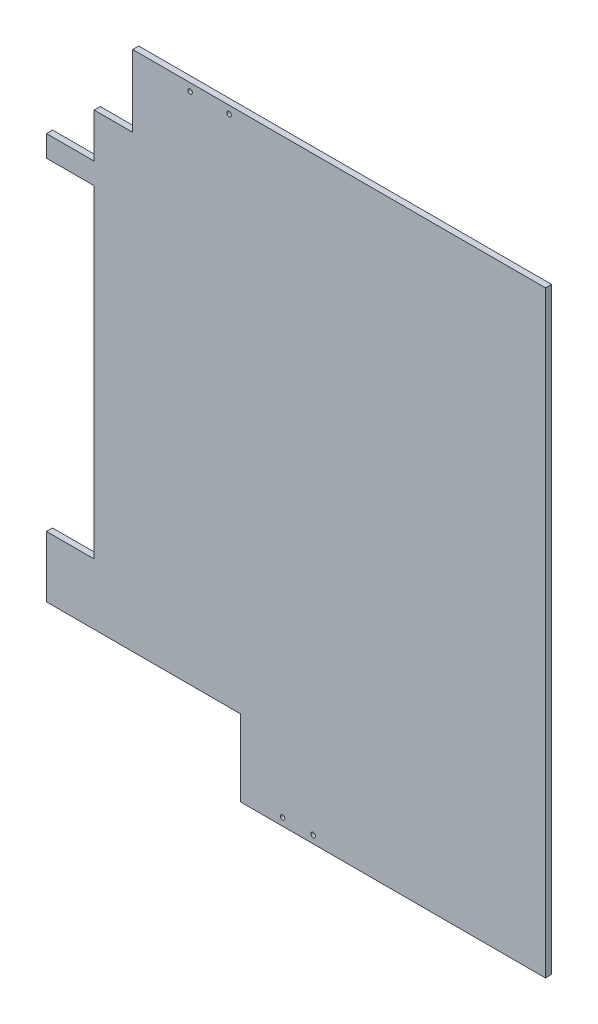
SolidWorks part; units mm, degrees
material "Balsa"
ref_plane "Front Plane" through (0, 0, 0) normal (0, 0, 1) x (1, 0, 0)
ref_plane "Top Plane" through (0, 0, 0) normal (0, 1, 0) x (1, 0, 0)
ref_plane "Right Plane" through (0, 0, 0) normal (1, 0, 0) x (0, 0, -1)
sketch "Sketch1" plane through (0, 0, 0) normal (0, 0, 1) x (1, 0, 0)
  line L0 (-5.7823, -13) -> (25.5, -13)
  line L2 (-5.7823, 1) -> (-5.7823, -13)
  line L5 (24.5, -14) -> (-24.5, -14) construction
  line L6 (321.5, -265) -> (321.5, 30)
  line L7 (-5.8246, -265) -> (65.6329, -265)
  line L8 (-5.8246, -265) -> (-5.8246, -225)
  line L11 (-5.8246, -265) -> (65.6329, -225) construction
  line L12 (-5.8246, -225) -> (65.6329, -265) construction
  line L15 (321.5, -265) -> (25.5, -265)
  line L16 (25.5, 1) -> (25.5, -265)
  line L17 (-5.8246, -225) -> (25.5, -225)
  line L18 (-24.5, -224) -> (24.5, -224) construction
  line L19 (-5.7823, 1) -> (25.5, 1)
  line L20 (24.5, -224) -> (24.5, -14) construction
  line L21 (-85.1981, 31) -> (50.7481, 31) construction
  line L23 (25.5, 1) -> (25.5, 30)
  line L24 (25.5, 30) -> (321.5, 30)
  line L27 (277.3251, 57) -> (277.3251, -295) construction
  line L28 (26.2777, -266) -> (-26.2882, -266) construction
  line L30 (-63.4467, 81) -> (255.5737, 81) construction
  line L31 (50.7481, 30) -> (321.5, 30)
  line L32 (50.7481, 30) -> (50.7481, 77)
  line L33 (50.7481, 77) -> (321.5, 77)
  line L34 (321.5, 30) -> (321.5, 77)
  line L35 (50.7481, 30) -> (321.5, 77) construction
  line L36 (50.7481, 77) -> (321.5, 30) construction
  line L37 (255.5737, -319) -> (-63.4467, -319) construction
  line L38 (321.5, -265) -> (121.5, -265)
  line L39 (321.5, -265) -> (321.5, -315)
  line L40 (321.5, -315) -> (121.5, -315)
  line L41 (121.5, -265) -> (121.5, -315)
  line L42 (321.5, -265) -> (121.5, -315) construction
  line L43 (321.5, -315) -> (121.5, -265) construction
  line L44 (50.7481, 31) -> (50.7481, -269) construction
  point P4 (32.4695, -6)
  point P10 (29.9042, -245)
  point P15 (48.1318, -132)
  point P24 (48.1318, 15.5)
  point P36 (186.1241, 53.5)
  point P42 (221.5, -290)
  dimension "D1" = 1
  dimension "D2" = 1
  dimension "D3" = 1
  dimension "D4" = 1
  dimension "D5" = 1
  dimension "D6" = 31.3246
  dimension "D7" = 296
  dimension "D8" = 4
  dimension "D9" = 200
  dimension "D10" = 4
extrude "Boss-Extrude1" add sketch "Sketch1" along normal blind 4 contours L24 L23 L16 L7 L15 L6 | L19 L2 L0 L16 | L17 L8 L7 L16 | L24 L34 L33 L32 | L15 L41 L40 L39
sketch "Sketch2" plane through (0, 0, 0) normal (0, 0, -1) x (-1, 0, 0)
  circle A0 centre (-113.9984, 72) radius 1.5
  circle A1 centre (-88.397, 72) radius 1.5
  circle A2 centre (-169.1689, -310) radius 1.5
  circle A3 centre (-149.0844, -310) radius 1.5
  dimension "D1" = 3
  dimension "D2" = 3
  dimension "D3" = 3
  dimension "D4" = 3
extrude "Cut-Extrude1" cut sketch "Sketch2" against normal through all
